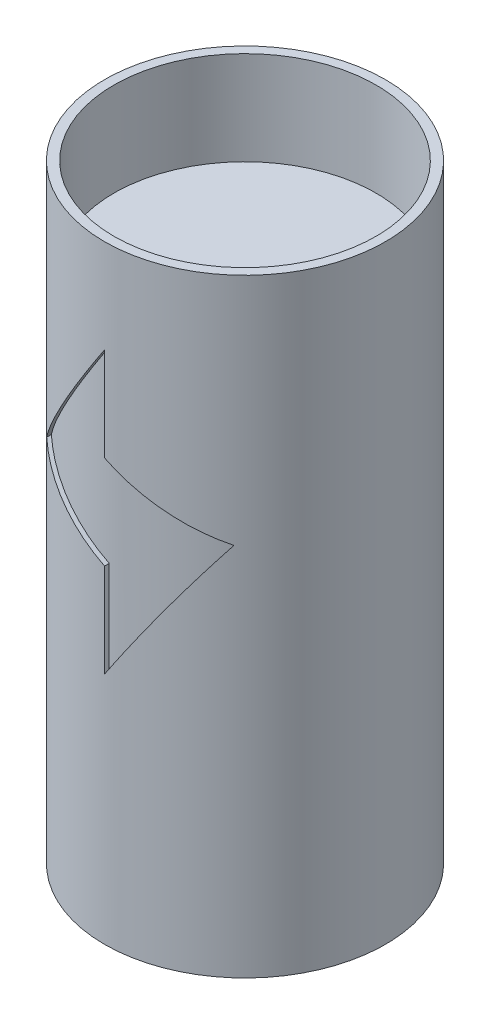
SolidWorks part; units mm, degrees
ref_plane "Front Plane" through (0, 0, 0) normal (0, 0, 1) x (1, 0, 0)
ref_plane "Top Plane" through (0, 0, 0) normal (0, 1, 0) x (1, 0, 0)
ref_plane "Right Plane" through (0, 0, 0) normal (1, 0, 0) x (0, 0, -1)
sketch "Sketch1" plane through (0, 0, 0) normal (0, 1, 0) x (1, 0, 0)
  circle A0 centre (0, 0) radius 60
  dimension "D1" = 120
extrude "Main Extrude" add sketch "Sketch1" along normal blind 260
sketch "Sketch2" plane through (0, 260, 0) normal (0, 1, 0) x (1, 0, 0)
  circle A0 centre (0, 0) radius 56
  circle A1 centre (0, 0) radius 60 construction
  dimension "D1" = 4
extrude "Hole for Blade Casing" cut sketch "Sketch2" against normal blind 40
sketch "Sketch3" plane through (0, 0, 0) normal (0, -1, 0) x (1, 0, 0)
  circle A0 centre (0, 0) radius 56
  circle A1 centre (0, 0) radius 60 construction
  dimension "D1" = 4
extrude "Hole to Hide Legs" cut sketch "Sketch3" against normal blind 20
ref_plane "Plane to Sketch Design" through (0, 0, 60) normal (0, 0, 1) x (1, 0, 0)
sketch "Sketch4" plane through (0, 0, 60) normal (0, 0, 1) x (1, 0, 0)
  line L0 (0, 220) -> (-40, 160)
  line L1 (-40, 160) -> (0, 140)
  line L2 (0, 140) -> (0, 100)
  line L3 (0, 100) -> (40, 160)
  line L4 (40, 160) -> (0, 180)
  line L5 (0, 180) -> (0, 220)
  line L6 (-60, 0) -> (60, 0) construction
  line L7 (-60, 260) -> (-60, 0) construction
  dimension "D1" = 100
  dimension "D2" = 120
  dimension "D3" = 60
  dimension "D4" = 60
  dimension "D5" = 60
  dimension "D6" = 60
  dimension "D7" = 40
  dimension "D8" = 40
  dimension "D9" = 40
  dimension "D10" = 40
  dimension "D11" = 40
extrude "Lightning Bolt" cut sketch "Sketch4" against normal blind 2 from surface starting at face at (0, 260, 60)
sketch "Sketch5" plane through (0, 20, 0) normal (0, -1, 0) x (1, 0, 0)
  line L0 (-24.7487, 24.7487) -> (24.7487, -24.7487) construction
  line L1 (24.7487, 24.7487) -> (-24.7487, -24.7487) construction
  line L2 (0, 35) -> (0, -35) construction
  line L3 (-35, 0) -> (35, 0) construction
  circle A0 centre (0, 0) radius 35 construction
  circle A1 centre (-24.7487, 24.7487) radius 16
  circle A2 centre (24.7487, 24.7487) radius 16
  circle A3 centre (24.7487, -24.7487) radius 16
  circle A4 centre (-24.7487, -24.7487) radius 16
  dimension "D1" = 70
  dimension "D4" = 32
  dimension "D5" = 32
  dimension "D6" = 32
  dimension "D7" = 32
  dimension "D2" = 45
  dimension "D3" = 45
extrude "Legs" add sketch "Sketch5" along normal blind 19
